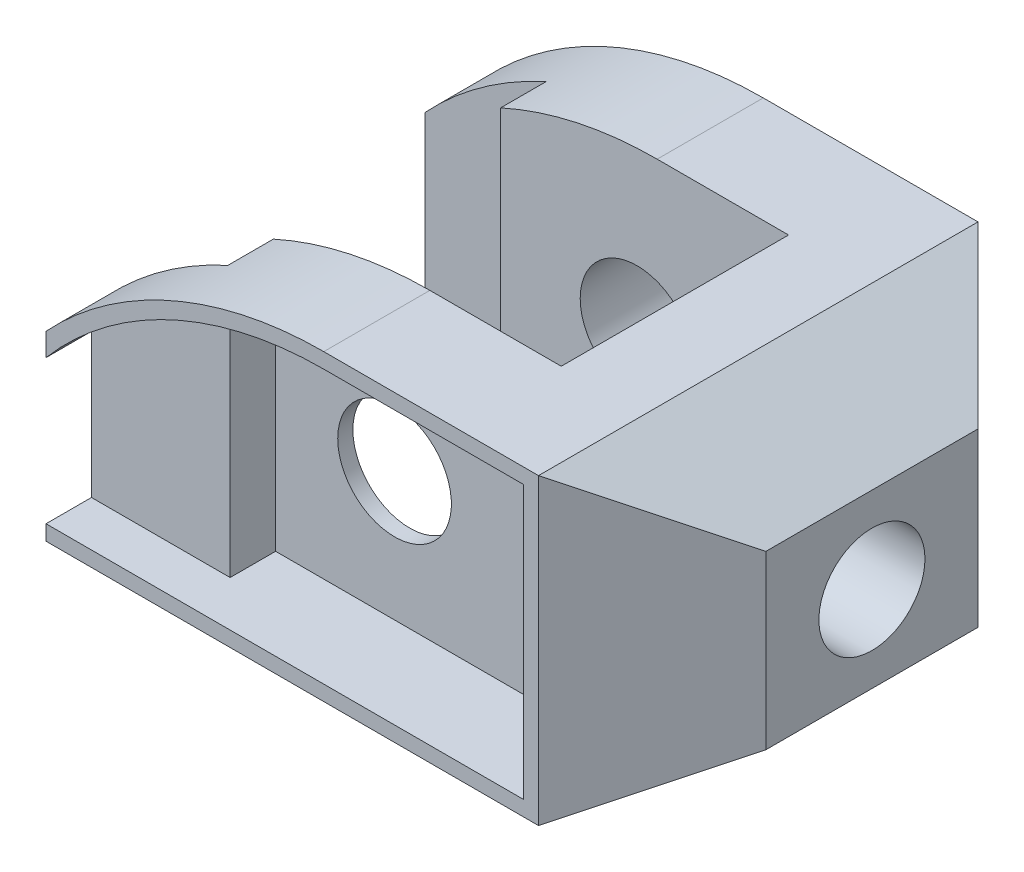
SolidWorks part; units mm, degrees
material "1060 Alloy"
ref_plane "Front Plane" through (0, 0, 0) normal (0, 0, 1) x (1, 0, 0)
ref_plane "Top Plane" through (0, 0, 0) normal (0, 1, 0) x (1, 0, 0)
ref_plane "Right Plane" through (0, 0, 0) normal (1, 0, 0) x (0, 0, -1)
sketch "Sketch1" plane through (0, 0, 0) normal (0, 0, 1) x (1, 0, 0)
  line L0 (0, 0) -> (65, 0)
  line L1 (65, 0) -> (80, 8.6603)
  line L2 (80, 8.6603) -> (80, 31.3397)
  line L3 (80, 31.3397) -> (65, 40)
  line L4 (65, 40) -> (36.6606, 40)
  line L5 (0, 0) -> (0, 24)
  arc A0 (0, 24) -> (36.6606, 40) centre (36.6606, -10) cw
  circle A1 centre (34, 19) radius 7.5
  dimension "D8" = 50
  dimension "D9" = 15
  dimension "D1" = 24
  dimension "D2" = 65
  dimension "D3" = 15
  dimension "D4" = 30
  dimension "D5" = 15
  dimension "D6" = 30
  dimension "D7" = 40
  dimension "D10" = 19
  dimension "D11" = 31
extrude "Boss-Extrude1" add sketch "Sketch1" along normal mid plane 58
sketch "Sketch2" plane through (0, 0, 0) normal (0, 1, 0) x (1, 0, 0)
  line L0 (0, -29) -> (0, 29) construction
  line L1 (0, 21) -> (16, 21)
  line L2 (0, 21) -> (0, -21)
  line L3 (0, -21) -> (16, -21)
  line L5 (36.6606, -29) -> (36.6606, 29) construction
  line L6 (16, -15) -> (54, -15)
  line L8 (16, 15) -> (54, 15)
  line L9 (54, -15) -> (54, 15)
  line L10 (0, -29) -> (36.6606, -29) construction
  line L11 (16, 21) -> (16, 15)
  line L12 (65, -29) -> (65, 29) construction
  line L13 (36.6606, 29) -> (0, 29) construction
  line L14 (16, -15) -> (16, -21)
  point P6 (36.6606, 0)
  dimension "D1" = 11
  dimension "D2" = 8
  dimension "D3" = 16
  dimension "D4" = 6
  dimension "D5" = 6
  dimension "D6" = 8
extrude "Cut-Extrude1" cut sketch "Sketch2" along normal blind 72
sketch "Sketch3" plane through (0, 0, 0) normal (0, 1, 0) x (1, 0, 0)
  line L0 (80, 29) -> (65, 29)
  line L1 (65, 29) -> (80, 14)
  line L2 (80, -29) -> (80, 29) construction
  line L3 (80, 14) -> (80, 29)
  line L4 (65, -29) -> (80, -29)
  line L5 (80, -29) -> (80, -14)
  line L6 (80, -14) -> (65, -29)
  dimension "D1" = 45
  dimension "D2" = 45
extrude "Cut-Extrude2" cut sketch "Sketch3" along normal blind 72
sketch "Sketch4" plane through (80, 0, 0) normal (1, 0, 0) x (0, 0, -1)
  line L0 (-29, 40) -> (-29, 0) construction
  line L1 (-29, 0) -> (29, 0) construction
  circle A0 centre (0, 20) radius 7
  dimension "D3" = 14
  dimension "D1" = 29
  dimension "D2" = 20
extrude "Cut-Extrude3" cut sketch "Sketch4" against normal blind 72
sketch "Sketch6" plane through (0, 0, 29) normal (0, 0, 1) x (1, 0, 0)
  line L1 (63, 2) -> (63, 38)
  line L2 (63, 38) -> (36.6606, 38)
  line L4 (65, 0) -> (65, 40)
  line L5 (65, 40) -> (36.6606, 40)
  line L6 (0, 24) -> (0, 0)
  line L7 (0, 0) -> (65, 0)
  line L8 (65, 0) -> (65, 40)
  line L9 (65, 40) -> (36.6606, 40)
  line L13 (18.3011, 2) -> (18.3011, 34.3501)
  line L15 (18.3011, 2) -> (63, 2)
  line L16 (0, 2) -> (63, 2) construction
  line L17 (0, 0) -> (65, 0) construction
  arc A0 (36.6606, 38) -> (18.3011, 34.3501) centre (36.6606, -10) ccw
  arc A1 (36.6606, 40) -> (0, 24) centre (36.6606, -10) ccw
  arc A4 (36.6606, 38) -> (1.4664, 22.64) centre (36.6606, -10) ccw construction
  arc A5 (36.6606, 40) -> (0, 24) centre (36.6606, -10) ccw construction
  point P12 (0, 0)
  dimension "D1" = 0
  dimension "D2" = 2
extrude "Cut-Extrude11" cut sketch "Sketch6" against normal blind 12 contours L13 A0 L2 L1 L15
sketch "Sketch8" plane through (0, 0, 29) normal (0, 0, 1) x (1, 0, 0)
  line L0 (0, 2) -> (18.3011, 2)
  line L3 (18.3011, 2) -> (18.3011, 34.3501) construction
  line L4 (65, 0) -> (65, 40)
  line L5 (65, 40) -> (36.6606, 40)
  line L6 (0, 24) -> (0, 0)
  line L7 (0, 0) -> (65, 0)
  line L10 (0, 20.9839) -> (0, 2)
  line L12 (18.3011, 2) -> (18.3011, 34.3501)
  arc A0 (18.3011, 34.3501) -> (0, 20.9839) centre (36.6606, -10) ccw
  arc A1 (36.6606, 40) -> (0, 24) centre (36.6606, -10) ccw
  dimension "D1" = 0
extrude "Cut-Extrude12" cut sketch "Sketch8" against normal blind 6
equation "\"A\"= 58mm"
equation "\"B\"= 40mm"
equation "\"C\"= 65mm"
equation "\"D2@Sketch1\"=\"C\""
equation "\"D7@Sketch1\"=\"B\""
equation "\"D1@Boss-Extrude1\"=\"A\""
equation "\"D2@Sketch4\"=\"B\"/2"
equation "\"D1@Sketch4\"=\"A\"/2"
